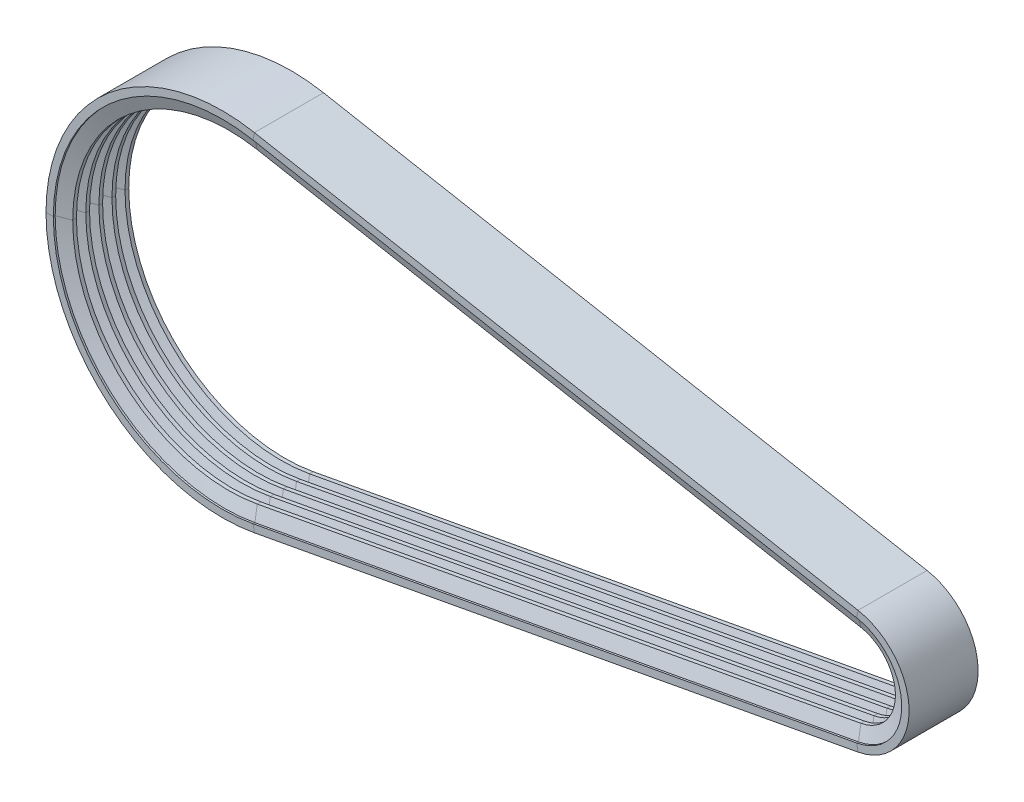
SolidWorks part; units mm, degrees
material "Эпихлоргидрин"
ref_plane "Спереди" through (0, 0, 0) normal (0, 0, 1) x (1, 0, 0)
ref_plane "Сверху" through (0, 0, 0) normal (0, 1, 0) x (1, 0, 0)
ref_plane "Справа" through (0, 0, 0) normal (1, 0, 0) x (0, 0, -1)
sketch "Эскиз1" plane through (0, 0, 0) normal (0, 0, 1) x (1, 0, 0)
  line L0 (-350.1512, 0) -> (178.9762, 0) construction
  line L1 (-161.2471, 47.1952) -> (3.1, 16.715)
  line L2 (-161.2471, -47.1952) -> (3.1, -16.715)
  arc A0 (3.1, -16.715) -> (3.1, 16.715) centre (0, 0) ccw
  arc A1 (-161.2471, 47.1952) -> (-161.2471, -47.1952) centre (-170, 0) ccw
  dimension "D1" = 34
  dimension "D2" = 96
  dimension "D3" = 170
sketch "Эскиз2" plane through (0, 0, 0) normal (0, 1, 0) x (1, 0, 0)
  line L1 (-212.5, 3.0539) -> (-216, 1.78)
  line L8 (-212.5, 4.0661) -> (-212.5, 3.0539)
  line L10 (-216, 5.34) -> (-212.5, 4.0661)
  line L11 (-218, 9.4) -> (-218, -9.4)
  line L12 (-218, 0) -> (-161.2471, 0) construction
  line L28 (-218, 0) -> (-174.5041, 0) construction
  line L29 (-218, 9.4) -> (-216, 9.4)
  line L32 (-216, 9.4) -> (-216, 8.9)
  line L33 (-216, 8.9) -> (-212.5, 7.6261)
  line L37 (-212.5, 7.6261) -> (-212.5, 6.6139)
  line L38 (-212.5, 6.6139) -> (-216, 5.34)
  line L39 (-206.1105, 7.12) -> (-201.097, 7.12) construction
  line L61 (-216, 10.4071) -> (-216, 1.0302) construction
  line L62 (-212.5, -0.5061) -> (-216, -1.78)
  line L63 (-212.5, 0.5061) -> (-212.5, -0.5061)
  line L64 (-216, 1.78) -> (-212.5, 0.5061)
  line L65 (-212.5, -4.0661) -> (-216, -5.34)
  line L66 (-212.5, -3.0539) -> (-212.5, -4.0661)
  line L67 (-216, -1.78) -> (-212.5, -3.0539)
  line L68 (-212.5, -7.6261) -> (-216, -8.9)
  line L69 (-212.5, -6.6139) -> (-212.5, -7.6261)
  line L70 (-216, -5.34) -> (-212.5, -6.6139)
  line L72 (-216, -9.4) -> (-216, -8.9)
  line L73 (-218, -9.4) -> (-216, -9.4)
  line L74 (-207.9045, 3.56) -> (49792.0955, 3.56) construction
  line L75 (-208, -3.56) -> (49792, -3.56) construction
  line L76 (-208, -7.12) -> (49792, -7.12) construction
  dimension "D6" = 5
  dimension "D1" = 18.8
  dimension "D2" = 3.56
  dimension "D3" = 5.5
  dimension "D4" = 40
  dimension "D5" = 2
sweep "По траектории1" add profiles "Эскиз2" path "Эскиз1"
